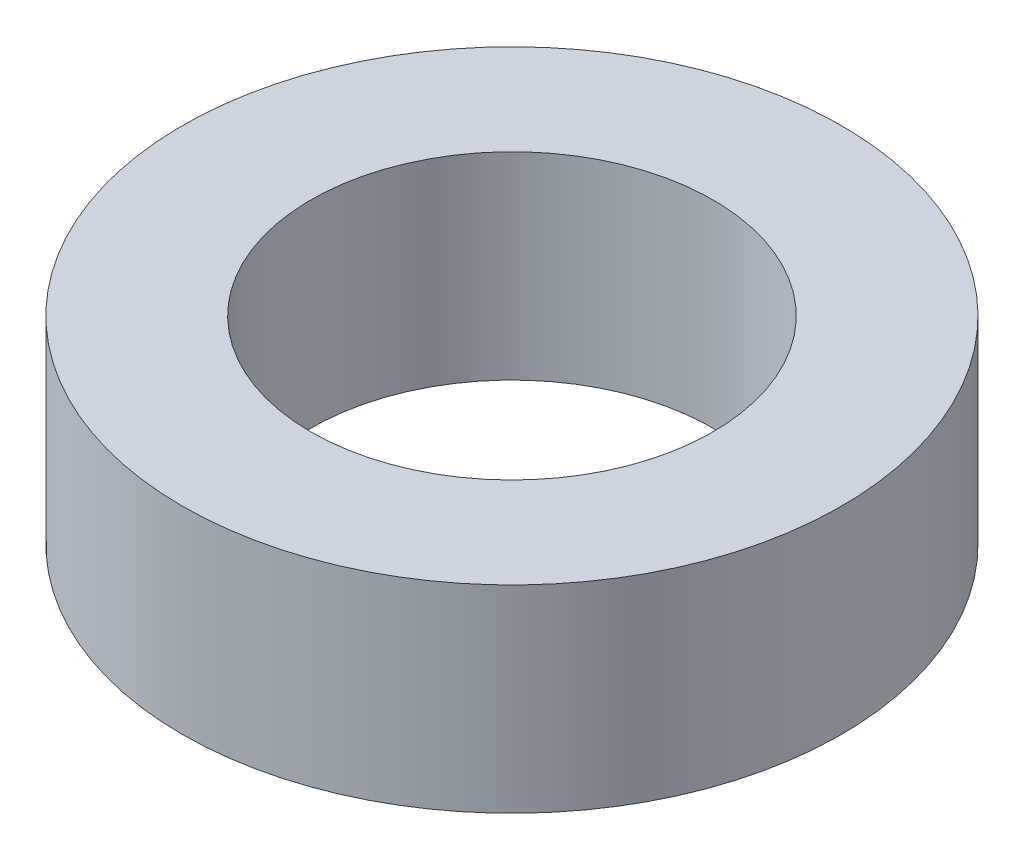
SolidWorks part; units mm, degrees
ref_plane "Front Plane" through (0, 0, 0) normal (0, 0, 1) x (1, 0, 0)
ref_plane "Top Plane" through (0, 0, 0) normal (0, 1, 0) x (1, 0, 0)
ref_plane "Right Plane" through (0, 0, 0) normal (1, 0, 0) x (0, 0, -1)
sketch "Sketch1" plane through (0, 0, 0) normal (0, 1, 0) x (1, 0, 0)
  circle A0 centre (0, 0) radius 3.05
  circle A1 centre (0, 0) radius 5
  dimension "D1" = 6.1
  dimension "D2" = 10
extrude "Boss-Extrude1" add sketch "Sketch1" along normal mid plane 3
